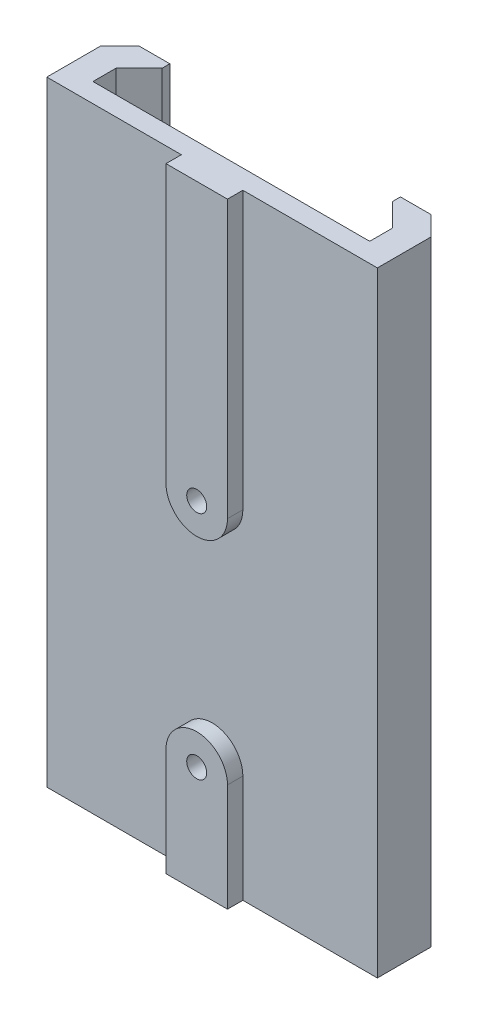
SolidWorks part; units mm, degrees
ref_plane "前视基准面" through (0, 0, 0) normal (0, 0, 1) x (1, 0, 0)
ref_plane "上视基准面" through (0, 0, 0) normal (0, 1, 0) x (1, 0, 0)
ref_plane "右视基准面" through (0, 0, 0) normal (1, 0, 0) x (0, 0, -1)
other "Configuration Table"
sketch "草图1" plane through (0, 0, 0) normal (0, 0, 1) x (1, 0, 0)
  line L1 (0, 0) -> (43, 0)
  line L2 (0, 0) -> (0, -80)
  line L3 (0, -80) -> (43, -80)
  line L4 (43, 0) -> (43, -80)
  dimension "D1" = 43
  dimension "D2" = 80
extrude "凸台-拉伸1" add sketch "草图1" along normal blind 9.5
sketch "草图2" plane through (0, 0, 0) normal (0, 1, 0) x (1, 0, 0)
  line L0 (6.5, 0) -> (6.5, -1)
  line L1 (43, 0) -> (0, 0) construction
  line L2 (6.5, -1) -> (3.5, -4)
  line L3 (3.5, -4) -> (3.5, -7)
  line L4 (3.5, -7) -> (39.5, -7)
  line L5 (21.5, 0) -> (21.5, -9.5) construction
  line L6 (43, -9.5) -> (0, -9.5) construction
  line L7 (39.5, -4) -> (39.5, -7)
  line L8 (36.5, 0) -> (36.5, -1)
  line L9 (36.5, -1) -> (39.5, -4)
  line L10 (6.5, 0) -> (36.5, 0)
  point P13 (21.5, -7)
  dimension "D1" = 15
  dimension "D2" = 1
  dimension "D3" = 18
  dimension "D4" = 3
  dimension "D5" = 7
extrude "切除-拉伸1" cut sketch "草图2" against normal through all
chamfer "倒角1" distance 2.5 angle 45 2 edges at (43, -40, 0) (0, -40, 0)
sketch "草图3" plane through (0, 0, 9.5) normal (0, 0, 1) x (1, 0, 0)
  line L0 (21.5, -80) -> (21.5, 0) construction
  line L1 (0, -80) -> (43, -80) construction
  line L2 (43, 0) -> (0, 0) construction
  line L6 (17.5, -80) -> (25.5, -80)
  line L7 (17.5, -36) -> (17.5, 0)
  line L8 (17.5, 0) -> (25.5, 0)
  line L9 (25.5, 0) -> (25.5, -36)
  line L10 (25.5, -66) -> (25.5, -80)
  line L11 (17.5, -66) -> (17.5, -80)
  arc A0 (17.5, -66) -> (25.5, -66) centre (21.5, -66) cw
  arc A1 (17.5, -36) -> (25.5, -36) centre (21.5, -36) ccw
  dimension "D1" = 8
  dimension "D2" = 30
  dimension "D3" = 14
extrude "凸台-拉伸2" add sketch "草图3" along normal blind 2
sketch "草图4" plane through (0, 0, 11.5) normal (0, 0, 1) x (1, 0, 0)
  circle A0 centre (21.5, -36) radius 1.3
  circle A1 centre (21.5, -66) radius 1.3
  dimension "D1" = 2.6
  dimension "D2" = 2.6
extrude "切除-拉伸2" cut sketch "草图4" against normal through all
sketch "草图5" plane through (0, 0, 7) normal (0, 0, -1) x (-1, 0, 0)
  circle A0 centre (-21.5, -36) radius 2.15
  circle A1 centre (-21.5, -66) radius 2.15
  dimension "D1" = 4.3
  dimension "D2" = 4.3
extrude "切除-拉伸3" cut sketch "草图5" against normal blind 1.8
sketch "草图7" plane through (0, 0, 0) normal (-1, 0, 0) x (0, 0, 1)
  line L0 (0, -80) -> (0, 0) construction
  line L3 (9.5, 0) -> (2.5, 0) construction
  circle A0 centre (5.2, -10) radius 1.25
  circle A1 centre (5.2, -25) radius 1.25
  circle A2 centre (5.2, -40) radius 1.25
  circle A3 centre (5.2, -55) radius 1.25
  circle A4 centre (5.2, -70) radius 1.25
  dimension "D1" = 2.5
  dimension "D2" = 5.2
  dimension "D3" = 10
  dimension "D4" = 5
extrude "切除-拉伸4" cut sketch "草图7" against normal blind 5
